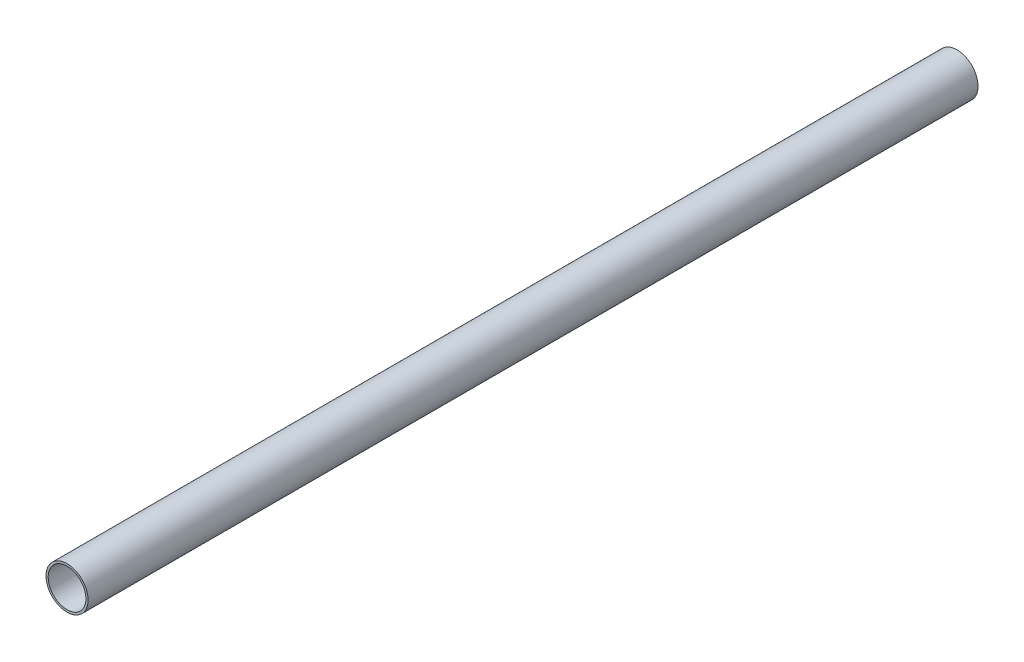
SolidWorks part; units mm, degrees
material "Copper"
ref_plane "Front" through (0, 0, 0) normal (0, 0, 1) x (1, 0, 0)
ref_plane "Top" through (0, 0, 0) normal (0, 1, 0) x (1, 0, 0)
ref_plane "Right" through (0, 0, 0) normal (1, 0, 0) x (0, 0, -1)
sketch "Sketch1" plane through (0, 0, 0) normal (0, 0, 1) x (1, 0, 0)
  circle A0 centre (0, 0) radius 11.1125
  circle A1 centre (0, 0) radius 9.9695
  dimension "D1" = 22.225
  dimension "D2" = 19.939
extrude "Boss-Extrude1" add sketch "Sketch1" along normal mid plane 470
